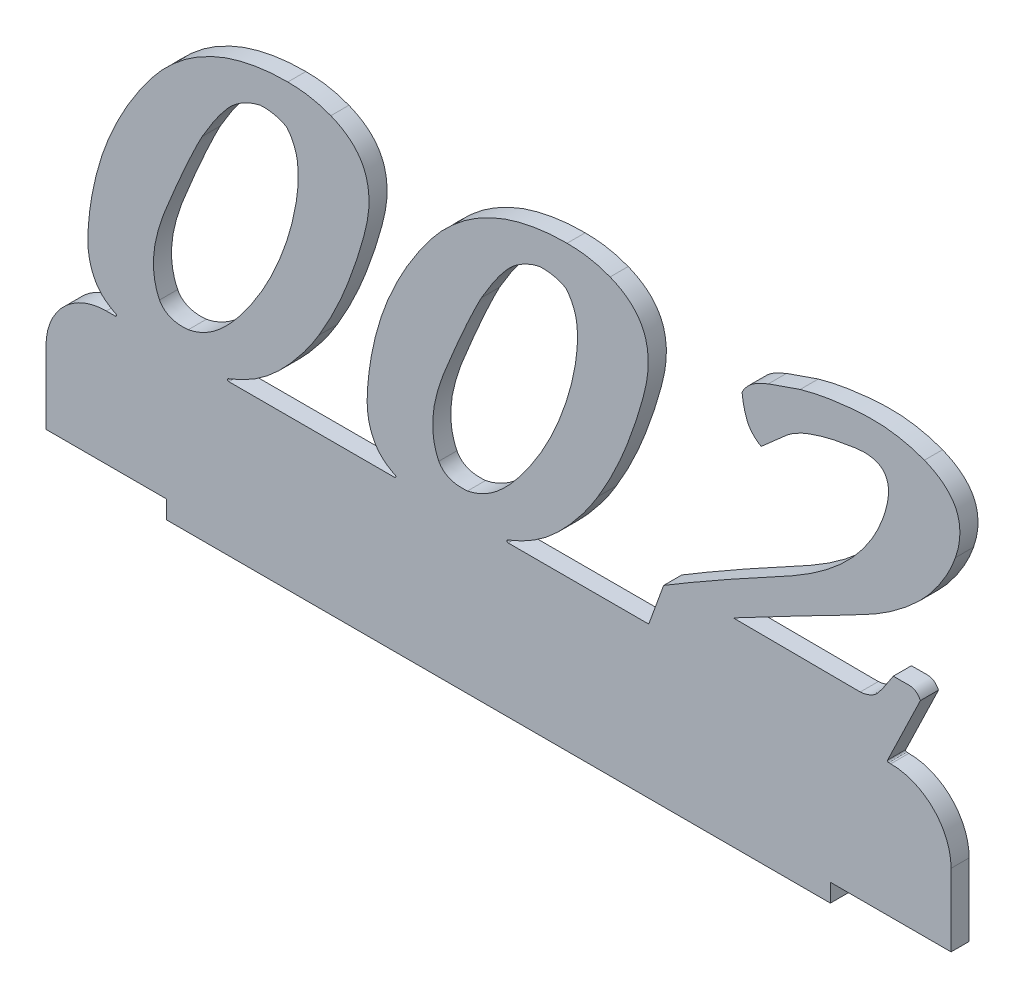
SolidWorks part; units mm, degrees
ref_plane "Front Plane" through (0, 0, 0) normal (0, 0, 1) x (1, 0, 0)
ref_plane "Top Plane" through (0, 0, 0) normal (0, 1, 0) x (1, 0, 0)
ref_plane "Right Plane" through (0, 0, 0) normal (1, 0, 0) x (0, 0, -1)
sketch "Sketch1" plane through (0, 0, 0) normal (0, 0, 1) x (1, 0, 0)
  line L0 (0, 20) -> (150, 20) construction
  line L1 (139.35, 22) -> (150, 22)
  line L2 (0, 22) -> (0, 0)
  line L3 (0, 0) -> (20, 0)
  line L4 (150, 22) -> (150, 0)
  line L5 (0, 22) -> (12.6118, 22)
  line L6 (144.917, 33.5372) -> (139.35, 22)
  line L8 (99.8944, 22) -> (102.3642, 28.7874)
  line L9 (122.8099, 60.5896) -> (118.5292, 56.8171)
  line L10 (113.9162, 29.9015) -> (134.9482, 29.7842)
  line L11 (130, 0) -> (150, 0)
  line L12 (29.1536, 22) -> (58.898, 22)
  line L13 (20, 0) -> (20, -3)
  line L14 (20, -3) -> (130, -3)
  line L15 (130, 0) -> (130, -3)
  line L16 (75.4397, 22) -> (99.8944, 22)
  spline S0 degree 3 poles (39.9326, 63.287) (39.3314, 63.6965) (37.8661, 64.2026) (36.3283, 64.3299) (35.5151, 64.2838) knots 0 0 0 0 0.469699 1 1 1 1
  spline S1 degree 3 poles (35.5151, 64.2838) (34.3704, 64.0432) (32.7524, 63.3656) (30.864, 61.9881) (28.5561, 59.41) (27.0224, 56.9584) (25.8787, 54.9797) knots 0 0 0 0 0.25259 0.375811 0.50377 1 1 1 1
  spline S2 degree 3 poles (25.8787, 54.9797) (25.4224, 54.1816) (24.8242, 52.8651) (23.9327, 51.046) (23.2192, 49.4645) (22.4548, 47.7452) (21.6543, 45.8785) (20.7977, 43.8823) (19.9257, 41.794) (19.1327, 39.6958) (18.501, 37.6685) (18.0602, 35.7614) (17.8173, 33.9683) (17.77, 32.289) (17.9717, 30.2633) (18.3912, 28.8397) (18.8224, 27.986) knots 0 0 0 0 0.095871 0.150957 0.21155 0.277044 0.347448 0.42366 0.503899 0.583776 0.657815 0.725493 0.787949 0.846481 0.90051 1 1 1 1
  spline S3 degree 3 poles (18.8224, 27.986) (19.1808, 27.2429) (20.6803, 26.0357) (22.5932, 26.0191) (23.5722, 26.0899) knots 0 0 0 0 0.446154 1 1 1 1
  spline S4 degree 3 poles (23.5722, 26.0899) (25.0297, 26.3643) (27.1863, 27.3827) (29.7186, 29.5505) (31.6691, 31.7077) (33.5359, 34.1932) (35.2974, 36.8672) (36.8878, 39.6937) (38.2824, 42.6499) (39.4805, 45.6669) (40.472, 48.679) (41.1907, 51.6675) (41.6953, 54.5581) (41.8649, 57.2598) (41.663, 60.2904) (40.7882, 62.279) (39.9326, 63.287) knots 0 0 0 0 0.099523 0.157976 0.224341 0.295662 0.367825 0.440561 0.514606 0.588508 0.65979 0.72866 0.796042 0.857776 0.911265 1 1 1 1
  spline S5 degree 3 poles (12.6118, 22) (12.1487, 22.1487) (11.2114, 22.493) (9.9552, 23.3102) (8.8453, 24.3292) (8.0154, 25.6065) (7.4099, 27.078) (6.8563, 29.4429) (6.9259, 31.3626) (7.0163, 32.6771) knots 0.508044 0.508044 0.508044 0.508044 0.5623 0.61932 0.674488 0.729675 0.788153 0.851799 1 1 1 1
  spline S6 degree 3 poles (7.0163, 32.6771) (7.1832, 34.9052) (7.6724, 38.2308) (8.8018, 42.5676) (9.8646, 45.777) (11.2192, 48.9103) (12.7572, 52.0161) (14.565, 55.0593) (16.572, 58.0264) (18.7696, 60.8158) (21.2438, 63.2346) (23.8861, 65.3222) (26.7663, 66.9696) (29.8018, 68.3174) (34.2242, 69.5398) (37.703, 69.9245) (40.0694, 69.8937) knots 0 0 0 0 0.122246 0.183381 0.245051 0.307032 0.370011 0.434579 0.500535 0.565958 0.62848 0.689454 0.749684 0.809559 0.870725 1 1 1 1
  spline S7 degree 3 poles (40.0694, 69.8937) (41.3297, 69.8833) (43.7725, 69.7397) (46.1127, 69.0299) (47.2039, 68.6232) knots 0 0 0 0 0.519885 1 1 1 1
  spline S8 degree 3 poles (47.2039, 68.6232) (48.4715, 68.1079) (50.2665, 67.1145) (52.0058, 65.1316) (52.9154, 63.4581) (53.4306, 61.5532) (53.5959, 59.4362) (53.4028, 57.1054) (52.6534, 53.766) (51.3749, 49.5996) (49.0737, 43.296) (46.8768, 38.8697) (45.2102, 36.1173) knots 0 0 0 0 0.111906 0.162582 0.212593 0.265416 0.321766 0.384451 0.454781 0.599581 0.738515 1 1 1 1
  spline S9 degree 3 poles (45.2102, 36.1173) (44.1187, 34.2601) (42.2484, 31.6896) (39.499, 28.5666) (37.3303, 26.4974) (34.9479, 24.6897) (32.2682, 23.1939) (30.2837, 22.3872) (29.2152, 22.0209) (29.1536, 22) knots 0 0 0 0 0.25786 0.380114 0.498337 0.616577 0.737567 0.865048 0.872848 0.872848 0.872848 0.872848
  spline S10 degree 3 poles (86.2188, 63.287) (85.6175, 63.6965) (84.1522, 64.2026) (82.6144, 64.3299) (81.8013, 64.2838) knots 0 0 0 0 0.469699 1 1 1 1
  spline S11 degree 3 poles (81.8013, 64.2838) (80.6566, 64.0432) (79.0385, 63.3656) (77.1501, 61.9881) (74.8422, 59.41) (73.3085, 56.9584) (72.1648, 54.9797) knots 0 0 0 0 0.25259 0.375811 0.50377 1 1 1 1
  spline S12 degree 3 poles (72.1648, 54.9797) (71.7085, 54.1816) (71.1103, 52.8651) (70.2188, 51.046) (69.5053, 49.4645) (68.741, 47.7452) (67.9405, 45.8785) (67.0839, 43.8823) (66.2118, 41.794) (65.4188, 39.6958) (64.7872, 37.6685) (64.3464, 35.7614) (64.1035, 33.9683) (64.0561, 32.289) (64.2579, 30.2633) (64.6774, 28.8397) (65.1085, 27.986) knots 0 0 0 0 0.095871 0.150957 0.21155 0.277044 0.347448 0.42366 0.503899 0.583776 0.657815 0.725493 0.787949 0.846481 0.90051 1 1 1 1
  spline S13 degree 3 poles (65.1085, 27.986) (65.467, 27.2429) (66.9665, 26.0357) (68.8794, 26.0191) (69.8583, 26.0899) knots 0 0 0 0 0.446154 1 1 1 1
  spline S14 degree 3 poles (69.8583, 26.0899) (71.3159, 26.3643) (73.4725, 27.3827) (76.0048, 29.5505) (77.9552, 31.7077) (79.822, 34.1932) (81.5835, 36.8672) (83.174, 39.6937) (84.5685, 42.6499) (85.7667, 45.6669) (86.7582, 48.679) (87.4769, 51.6675) (87.9814, 54.5581) (88.151, 57.2598) (87.9492, 60.2904) (87.0743, 62.279) (86.2188, 63.287) knots 0 0 0 0 0.099523 0.157976 0.224341 0.295662 0.367825 0.440561 0.514606 0.588508 0.65979 0.72866 0.796042 0.857776 0.911265 1 1 1 1
  spline S15 degree 3 poles (58.898, 22) (58.4349, 22.1487) (57.4976, 22.493) (56.2414, 23.3102) (55.1314, 24.3292) (54.3016, 25.6065) (53.6961, 27.078) (53.1425, 29.4429) (53.2121, 31.3626) (53.3024, 32.6771) knots 0.508044 0.508044 0.508044 0.508044 0.5623 0.61932 0.674488 0.729675 0.788153 0.851799 1 1 1 1
  spline S16 degree 3 poles (53.3024, 32.6771) (53.4694, 34.9052) (53.9585, 38.2308) (55.0879, 42.5676) (56.1508, 45.777) (57.5054, 48.9103) (59.0434, 52.0161) (60.8511, 55.0593) (62.8582, 58.0264) (65.0557, 60.8158) (67.53, 63.2346) (70.1723, 65.3222) (73.0525, 66.9696) (76.088, 68.3174) (80.5104, 69.5398) (83.9891, 69.9245) (86.3556, 69.8937) knots 0 0 0 0 0.122246 0.183381 0.245051 0.307032 0.370011 0.434579 0.500535 0.565958 0.62848 0.689454 0.749684 0.809559 0.870725 1 1 1 1
  spline S17 degree 3 poles (86.3556, 69.8937) (87.6158, 69.8833) (90.0587, 69.7397) (92.3988, 69.0299) (93.4901, 68.6232) knots 0 0 0 0 0.519885 1 1 1 1
  spline S18 degree 3 poles (93.4901, 68.6232) (94.7576, 68.1079) (96.5527, 67.1145) (98.292, 65.1316) (99.2015, 63.4581) (99.7168, 61.5532) (99.8821, 59.4362) (99.689, 57.1054) (98.9396, 53.766) (97.6611, 49.5996) (95.3599, 43.296) (93.163, 38.8697) (91.4963, 36.1173) knots 0 0 0 0 0.111906 0.162582 0.212593 0.265416 0.321766 0.384451 0.454781 0.599581 0.738515 1 1 1 1
  spline S19 degree 3 poles (91.4963, 36.1173) (90.4048, 34.2601) (88.5346, 31.6896) (85.7852, 28.5666) (83.6165, 26.4974) (81.2341, 24.6897) (78.5544, 23.1939) (76.5699, 22.3872) (75.5014, 22.0209) (75.4397, 22) knots 0 0 0 0 0.25786 0.380114 0.498337 0.616577 0.737567 0.865048 0.872848 0.872848 0.872848 0.872848
  spline S20 degree 3 poles (102.3642, 28.7874) (103.7733, 29.6358) (105.9565, 30.9476) (108.9989, 32.6804) (111.4694, 34.1151) (114.0953, 35.576) (116.8609, 37.1017) (119.7559, 38.7118) (122.7796, 40.3006) (125.7246, 41.9879) (128.4311, 43.8154) (130.8726, 45.7028) (133.0152, 47.7085) (134.882, 49.7966) (136.9527, 52.6716) (138.1553, 54.9998) (138.7207, 56.6216) knots 0 0 0 0 0.105525 0.163386 0.224617 0.288806 0.356162 0.427253 0.501314 0.575301 0.644862 0.710669 0.773069 0.83288 0.890073 1 1 1 1
  spline S21 degree 3 poles (138.7207, 56.6216) (139.1504, 57.8571) (139.6796, 59.6058) (139.6303, 61.8276) (139.191, 63.0295) (138.3735, 63.9292) (137.1601, 64.4012) (135.661, 64.5824) (133.9209, 64.3939) (132.1029, 64.0841) (130.3375, 63.7451) (128.729, 63.3285) (127.2612, 62.8801) (125.9271, 62.4045) (124.4214, 61.693) (123.3907, 61.0863) (122.8099, 60.5896) knots 0 0 0 0 0.163534 0.223587 0.273098 0.319543 0.36998 0.431294 0.506061 0.586527 0.660902 0.729495 0.793065 0.851774 0.905429 1 1 1 1
  spline S22 degree 3 poles (118.5292, 56.8171) (117.9983, 57.1169) (117.0725, 57.8422) (116.4265, 58.8255) (116.2227, 59.3386) knots 0 0 0 0 0.525688 1 1 1 1
  spline S23 degree 2 poles (116.2227, 59.3386) (115.5136, 61.1196) (115.3626, 63.0329) knots 0 0 0 1 1 1
  spline S24 degree 3 poles (115.3626, 63.0329) (115.7412, 63.7948) (117.0074, 65.2517) (118.7732, 66.0156) (119.7215, 66.3949) knots 0 0 0 0 0.45102 1 1 1 1
  spline S25 degree 2 poles (119.7215, 66.3949) (122.3416, 67.3672) (124.9991, 68.2322) knots 0 0 0 1 1 1
  spline S26 degree 3 poles (124.9991, 68.2322) (126.6223, 68.6998) (129.1413, 69.2188) (132.5884, 69.6878) (135.276, 69.8964) (137.9773, 69.9719) (141.4631, 69.6175) (143.99, 68.9961) (145.5816, 68.3691) knots 0 0 0 0 0.24204 0.368376 0.498665 0.628562 0.755291 1 1 1 1
  spline S27 degree 3 poles (145.5816, 68.3691) (146.7589, 67.8906) (148.4071, 67.0142) (150.0686, 65.32) (150.9214, 63.9415) (151.3929, 62.3878) (151.5702, 60.0047) (151.154, 58.1673) (150.7223, 56.9539) knots 0 0 0 0 0.269969 0.386879 0.498158 0.609266 0.726759 1 1 1 1
  spline S28 degree 3 poles (150.7223, 56.9539) (150.1525, 55.2954) (148.9263, 52.9345) (146.8547, 50.0227) (145.003, 47.936) (142.854, 45.9912) (140.4635, 44.1249) (137.795, 42.3807) (133.922, 40.2955) (129.1123, 37.8723) (122.1286, 34.2149) (117.0989, 31.6139) (113.9162, 29.9015) knots 0 0 0 0 0.112096 0.169586 0.228764 0.29055 0.355137 0.423026 0.494633 0.636984 0.76832 1 1 1 1
  spline S29 degree 3 poles (134.9482, 29.7842) (135.6072, 29.8424) (136.5811, 30.0668) (137.6355, 30.8116) (138.869, 32.2987) (139.6568, 33.7187) (140.4213, 34.7881) knots 0 0 0 0 0.257232 0.374596 0.49231 1 1 1 1
  spline S30 degree 3 poles (140.4213, 34.7881) (141.2733, 34.7498) (142.3111, 34.8367) (143.5657, 34.7898) (144.3354, 34.4391) (144.7211, 33.9128) (144.917, 33.5372) knots 0 0 0 0 0.506825 0.628241 0.743426 1 1 1 1
  dimension "D1" = 150
  dimension "D2" = 3
  dimension "D3" = 20
  dimension "D4" = 20
  dimension "D5" = 20
extrude "Boss-Extrude1" add sketch "Sketch1" along normal blind 3
fillet "Fillet1" radius 10 2 edges at (0, 22, 1.5) (150, 22, 1.5)
fillet "Fillet2" radius 0.2 6 edges at (12.6118, 22, 1.5) (58.898, 22, 1.5) (99.8944, 22, 1.5) (139.35, 22, 1.5) (75.4397, 22, 1.5) (29.1536, 22, 1.5)
